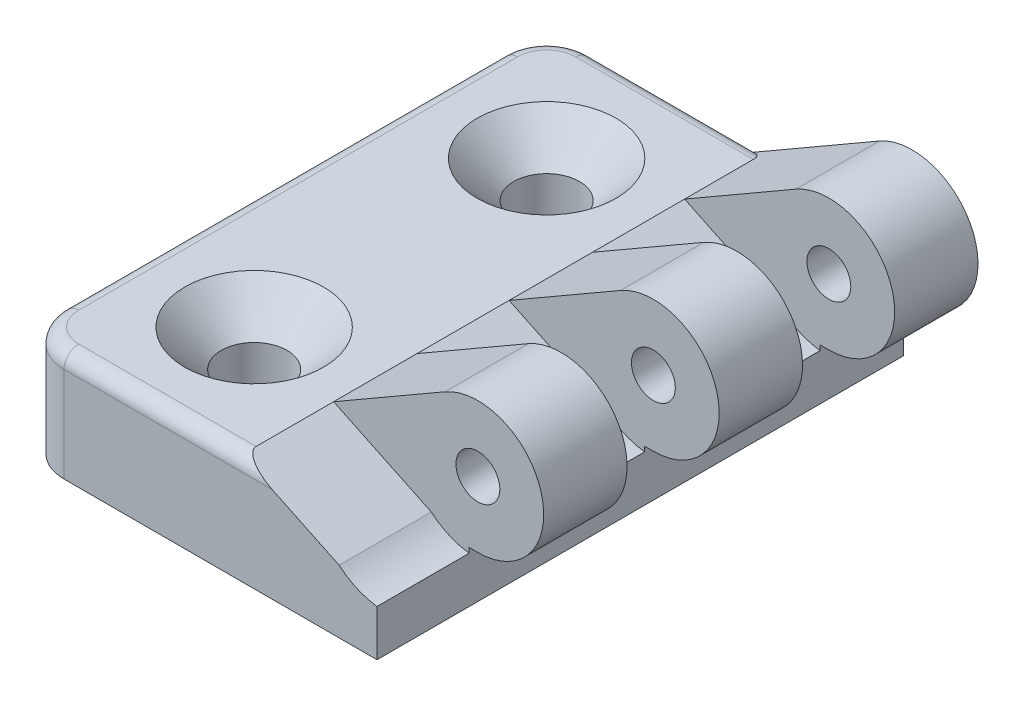
SolidWorks part; units mm, degrees
ref_plane "Front Plane" through (0, 0, 0) normal (0, 0, 1) x (1, 0, 0)
ref_plane "Top Plane" through (0, 0, 0) normal (0, 1, 0) x (1, 0, 0)
ref_plane "Right Plane" through (0, 0, 0) normal (1, 0, 0) x (0, 0, -1)
sketch "Croquis1" plane through (0, 0, 0) normal (0, 0, 1) x (1, 0, 0)
  line L0 (12.75, 7.8971) -> (5.134, 3.5)
  line L1 (-10, -4) -> (14.4, -4)
  line L2 (-10, -4) -> (-10, 3.5)
  line L3 (-10, 3.5) -> (5.134, 3.5)
  line L4 (15, -0.5) -> (14.4, -0.5)
  line L5 (-10, -4) -> (15, 4) construction
  line L6 (-10, 3.5) -> (18.6783, -4.5299) construction
  line L8 (14.4, -0.5) -> (14.4, -4)
  arc A0 (15, -0.5) -> (12.75, 7.8971) centre (15, 4) ccw
  circle A1 centre (15, 4) radius 1.5
  point P0 (2.5, 0)
  dimension "D3" = 3
  dimension "D4" = 4.5
  dimension "D1" = 7.5
  dimension "D2" = 25
  dimension "D5" = 30
  dimension "D6" = 0.6
  dimension "D7" = 3.5
extrude "Saliente-Extruir1" add sketch "Croquis1" against normal blind 36
sketch "Croquis2" plane through (0, 0, 0) normal (0, 0, 1) x (1, 0, 0)
  line L1 (14.4, -0.8426) -> (15, -0.5)
  line L2 (5.134, 3.5) -> (11.8076, 0.3095)
  line L3 (14.4, -4) -> (14.4, -0.5) construction
  line L5 (12.75, 7.8971) -> (5.134, 3.5) construction
  line L7 (12.75, 7.8971) -> (5.134, 3.5)
  arc A0 (15, -0.5) -> (12.75, 7.8971) centre (15, 4) ccw construction
  arc A1 (14.4, -0.8426) -> (11.8076, 0.3095) centre (15, 4) cw
  arc A2 (15, -0.5) -> (12.75, 7.8971) centre (15, 4) ccw
extrude "Cortar-Extruir1" cut sketch "Croquis2" against normal blind 6.3
pattern_linear "MatrizL1" count 3 spacing 12 along (0, 0, -1) of "Cortar-Extruir1"
sketch "Croquis3" plane through (0, 3.5, 0) normal (0, 1, 0) x (1, 0, 0)
  line L0 (-2, 28) -> (-2, 8) construction
  line L1 (5.134, 36) -> (-10, 36) construction
  line L2 (-10, 36) -> (-10, 0) construction
  circle A0 centre (-2, 28) radius 2.25
  circle A1 centre (-2, 8) radius 2.25
  dimension "D1" = 4.5
  dimension "D2" = 4.5
  dimension "D3" = 20
  dimension "D4" = 8
  dimension "D5" = 8
extrude "Cortar-Extruir2" cut sketch "Croquis3" against normal through all
chamfer "Chaflán1" distance 2.5 angle 45 2 edges at (-2, 3.5, -5.75) (-2, 3.5, -25.75)
fillet "Redondeo1" radius 3 2 edges at (-10, -0.25, 0) (-10, -0.25, -36)
fillet "Redondeo2" radius 1 5 edges at (-0.933, 3.5, -36) (-9.1213, 3.5, -35.1213) (-0.933, 3.5, 0) (-9.1213, 3.5, -0.8787) (-10, 3.5, -18)
equation "\"num_dents\"= 3"
equation "\"gap\"= .6"
equation "\"llarg\"= 36"
equation "\"D1@Saliente-Extruir1\"=\"llarg\""
equation "\"D1@Cortar-Extruir1\"=(\"llarg\"-\"num_dents\"*\"gap\")/(2*\"num_dents\")+\"gap\""
equation "\"D1@MatrizL1\"=\"num_dents\""
equation "\"D3@MatrizL1\"=\"llarg\"/\"num_dents\""
equation "\"D2@Croquis3\"=\"D1@Croquis3\""
equation "\"D4@Croquis3\"=(\"llarg\"-\"D3@Croquis3\")/2"
equation "\"D5@Croquis3\"=\"D4@Croquis3\""
